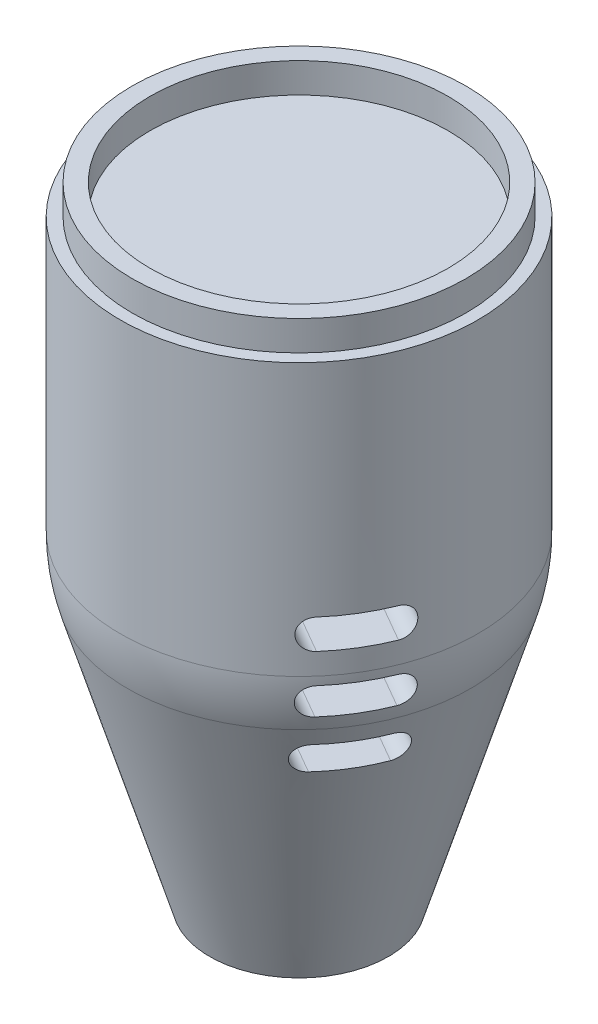
SolidWorks part; units mm, degrees
ref_plane "Front Plane" through (0, 0, 0) normal (0, 0, 1) x (1, 0, 0)
ref_plane "Top Plane" through (0, 0, 0) normal (0, 1, 0) x (1, 0, 0)
ref_plane "Right Plane" through (0, 0, 0) normal (1, 0, 0) x (0, 0, -1)
sketch "Sketch3" plane through (0, 0, 0) normal (0, 0, 1) x (1, 0, 0)
  line L0 (0, 0) -> (0, 100)
  line L1 (0, 0) -> (15, 0)
  line L2 (0, 100) -> (30, 100)
  line L3 (30, 100) -> (30, 54.4031)
  line L4 (28.7348, 45.7826) -> (15, 0)
  arc A0 (30, 54.4031) -> (28.7348, 45.7826) centre (0, 54.4031) cw
  point P7 (30, 50)
  dimension "D5" = 30
  dimension "D1" = 100
  dimension "D2" = 30
  dimension "D3" = 50
  dimension "D4" = 15
revolve "Revolve1" add sketch "Sketch3" angle 360 about L0
sketch "Sketch4" plane through (0, 100, 0) normal (0, 1, 0) x (1, 0, 0)
  circle A2 centre (0, 0) radius 28
  circle A3 centre (0, 0) radius 28
  dimension "D1" = 2
extrude "Extrude-Thin1" add sketch "Sketch4" along normal blind 5 thin thin type one direction reverse wall 3
sketch "Sketch9" plane through (0, 0, 0) normal (0, 0, 1) x (1, 0, 0)
  line L0 (0.7437, 0.4923) -> (0.7437, 105) construction
  line L1 (-4.2563, 62.9923) -> (5.7437, 62.9923)
  line L2 (-4.2563, 57.9923) -> (5.7437, 57.9923)
  arc A0 (5.7437, 62.9923) -> (5.7437, 57.9923) centre (5.7437, 60.4923) cw
  arc A1 (-4.2563, 62.9923) -> (-4.2563, 57.9923) centre (-4.2563, 60.4923) ccw
  point P2 (0.7437, 57.9923)
  point P10 (0.7437, 62.9923)
  dimension "D3" = 5
  dimension "D1" = 10
  dimension "D2" = 60
extrude "Cut-Extrude1" cut sketch "Sketch9" against normal through all
pattern_linear "LPattern1" count 3 spacing 10 along (0, -1, 0) of "Cut-Extrude1"
pattern_circular "CirPattern7" count 3 every 120 about axis through (0, 0, 0) along (0, -1, 0) of "LPattern1", "Cut-Extrude1"
